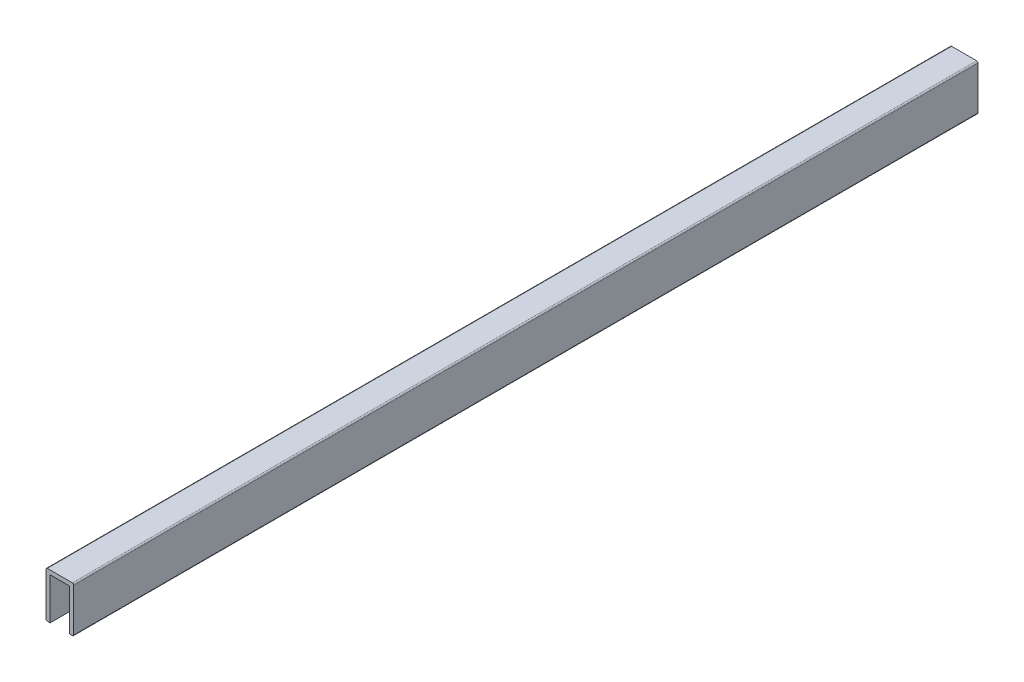
SolidWorks part; units mm, degrees
material "2014-O"
ref_plane "Front Plane" through (0, 0, 0) normal (0, 0, 1) x (1, 0, 0)
ref_plane "Top Plane" through (0, 0, 0) normal (0, 1, 0) x (1, 0, 0)
ref_plane "Right Plane" through (0, 0, 0) normal (1, 0, 0) x (0, 0, -1)
sketch "Sketch1" plane through (0, 0, 0) normal (0, 0, 1) x (1, 0, 0)
  line L0 (-5, -7.5) -> (-5, 9)
  line L1 (-3.5, -7.5) -> (3.5, -7.5) construction
  line L2 (-3.5, -7.5) -> (-3.5, 7.5)
  line L3 (-3.5, 7.5) -> (3.5, 7.5)
  line L4 (3.5, -7.5) -> (3.5, 7.5)
  line L5 (-3.5, -7.5) -> (3.5, 7.5) construction
  line L6 (-3.5, 7.5) -> (3.5, -7.5) construction
  line L7 (-5, 9) -> (5, 9)
  line L8 (5, -7.5) -> (5, 9)
  line L9 (-3.5, -7.5) -> (-5, -7.5)
  line L10 (3.5, -7.5) -> (5, -7.5)
  point P0 (0, 0)
  dimension "D1" = 7
  dimension "D2" = 15
  dimension "D3" = 1.5
extrude "Boss-Extrude1" add sketch "Sketch1" along normal blind 326
fillet "Fillet1" radius 0.5 4 edges at (5, -7.5, 163) (-5, -7.5, 163) (-5, 9, 163) (5, 9, 163)
